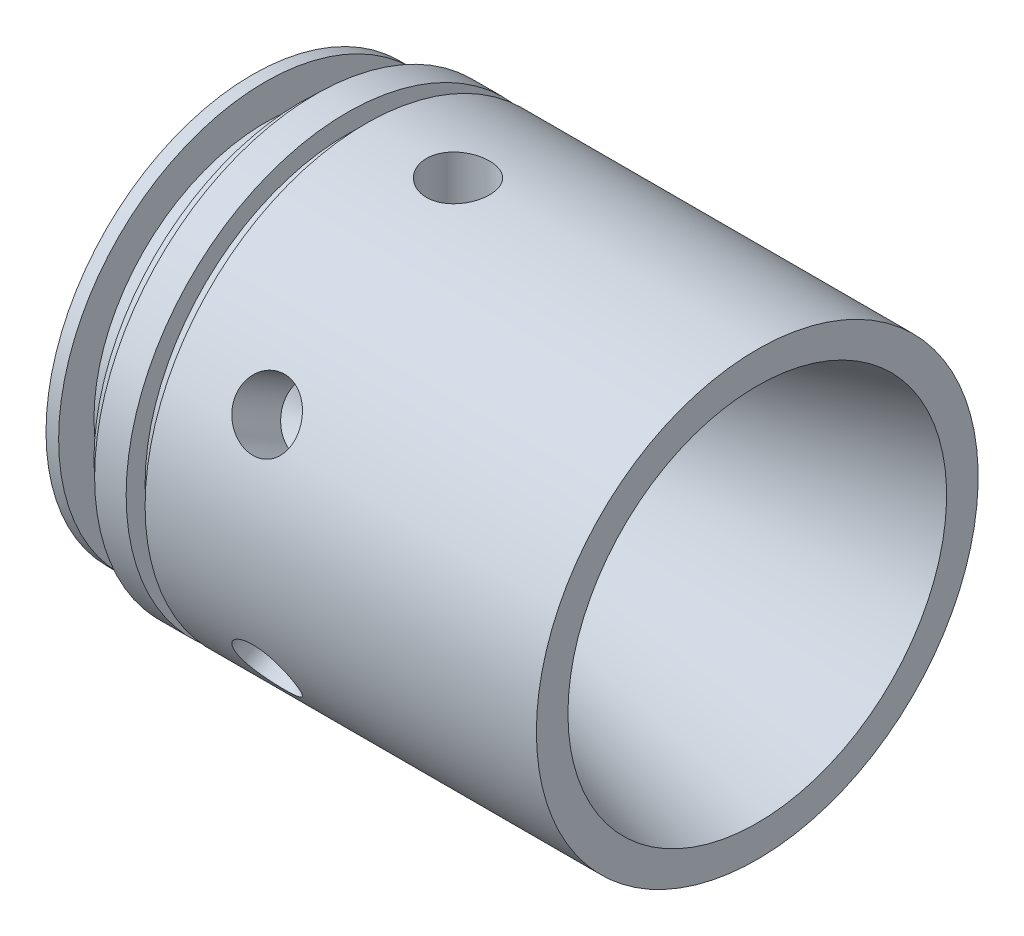
SolidWorks part; units mm, degrees
material "AISI 304"
ref_plane "Front Plane" through (0, 0, 0) normal (0, 0, 1) x (1, 0, 0)
ref_plane "Top Plane" through (0, 0, 0) normal (0, 1, 0) x (1, 0, 0)
ref_plane "Right Plane" through (0, 0, 0) normal (1, 0, 0) x (0, 0, -1)
sketch "Sketch2" plane through (0, 0, 0) normal (0, 0, 1) x (1, 0, 0)
  line L0 (0, 0) -> (0, 19.05) construction
  line L11 (0, 19.05) -> (-20.32, 31.75)
  line L12 (81.28, 0) -> (81.28, 38.1) construction
  line L13 (-20.32, 44.45) -> (-7.62, 44.45)
  line L14 (-20.32, 44.45) -> (-20.32, 41.529)
  line L15 (-20.32, 41.529) -> (-7.62, 41.529)
  line L16 (-7.62, 41.529) -> (-7.62, 44.45)
  line L17 (-17.78, 41.529) -> (-17.78, 34.417)
  line L18 (-10.16, 25.4) -> (15.24, 25.4)
  line L22 (-20.32, 31.75) -> (-20.32, 44.45)
  line L23 (0, 0) -> (81.28, 0) construction
  line L25 (19.6574, 20.9826) -> (15.24, 25.4)
  line L27 (-20.32, 44.45) -> (0, 44.45)
  line L28 (-17.78, 34.417) -> (-10.668, 34.417)
  line L29 (-10.668, 34.417) -> (-10.668, 41.529)
  line L30 (81.28, 44.45) -> (0, 44.45)
  line L36 (-1.27, 44.45) -> (2.54, 44.45)
  line L37 (-1.27, 44.45) -> (-1.27, 40.64)
  line L38 (-1.27, 40.64) -> (2.54, 40.64)
  line L39 (2.54, 44.45) -> (2.54, 40.64)
  line L40 (0, 19.05) -> (12.7, 19.05)
  line L43 (81.28, 44.45) -> (81.28, 38.1)
  line L44 (12.7, 19.05) -> (81.28, 38.1)
  line L45 (-12.192, 26.67) -> (15.7661, 26.67)
  line L46 (15.7661, 26.67) -> (21.063, 21.3731)
  dimension "D1" = 19.05
  dimension "D2" = 20.32
  dimension "D4" = 45
  dimension "D5" = 31.75
  dimension "D15" = 25.4
  dimension "D3" = 12.7
  dimension "D6" = 68.58
  dimension "D7" = 38.1
  dimension "D8" = 41.529
  dimension "D9" = 7.112
  dimension "D10" = 7.112
  dimension "D11" = 2.54
  dimension "D12" = 6.35
  dimension "D13" = 3.81
  dimension "D14" = 3.81
  dimension "D16" = 12.7
  dimension "D18" = 1.27
  dimension "D19" = 44.45
  dimension "D20" = 1.27
  dimension "D17" = 25.4
  dimension "D21" = 34.417
revolve "Revolve2" add sketch "Sketch2" angle 360 about L23
ref_plane "Plane1" through (0, 44.45, 0) normal (0, 1, 0) x (1, 0, 0)
sketch "Sketch3" plane through (0, 44.45, 0) normal (0, 1, 0) x (1, 0, 0)
  line L3 (21.063, -21.3731) -> (21.063, 21.3731) construction
  circle A0 centre (21.063, 0) radius 3.175
  point P0 (21.063, 0)
  point P19 (0, 0)
  point P22 (0, 0)
  point P23 (0, 0)
  dimension "D1" = 6.35
hole_wizard "1/2 (0.5) Diameter Hole1" positions "Sketch3" profile "Sketch4" hole size "1/2" standard "ANSI Inch"
sketch "Sketch4" plane through (21.063, 44.45, 0) normal (1, 0, 0) x (0, 0, 1)
  line L0 (0, 0) -> (0, 15.24)
  line L1 (0, 15.24) -> (6.35, 11.4245)
  line L2 (6.35, 11.4245) -> (6.35, 0)
  line L5 (6.35, 0) -> (0, 0)
  line L10 (0, 15.24) -> (-6.35, 11.4245) construction
  line L11 (0, -6.35) -> (0, 107.95) construction
  dimension "Hole Dia." = 12.7
  dimension "Hole Depth" = 15.24
  dimension "Drill Angle" = 118
sketch "Sketch5" plane through (0, 0, 0) normal (0, 0, 1) x (1, 0, 0)
  line L0 (0, 0) -> (70.9026, 0) construction
pattern_circular "CirPattern1" count 6 over 360 about axis through (0, 0, 0) along (1, 0, 0) of "1/2 (0.5) Diameter Hole1"
